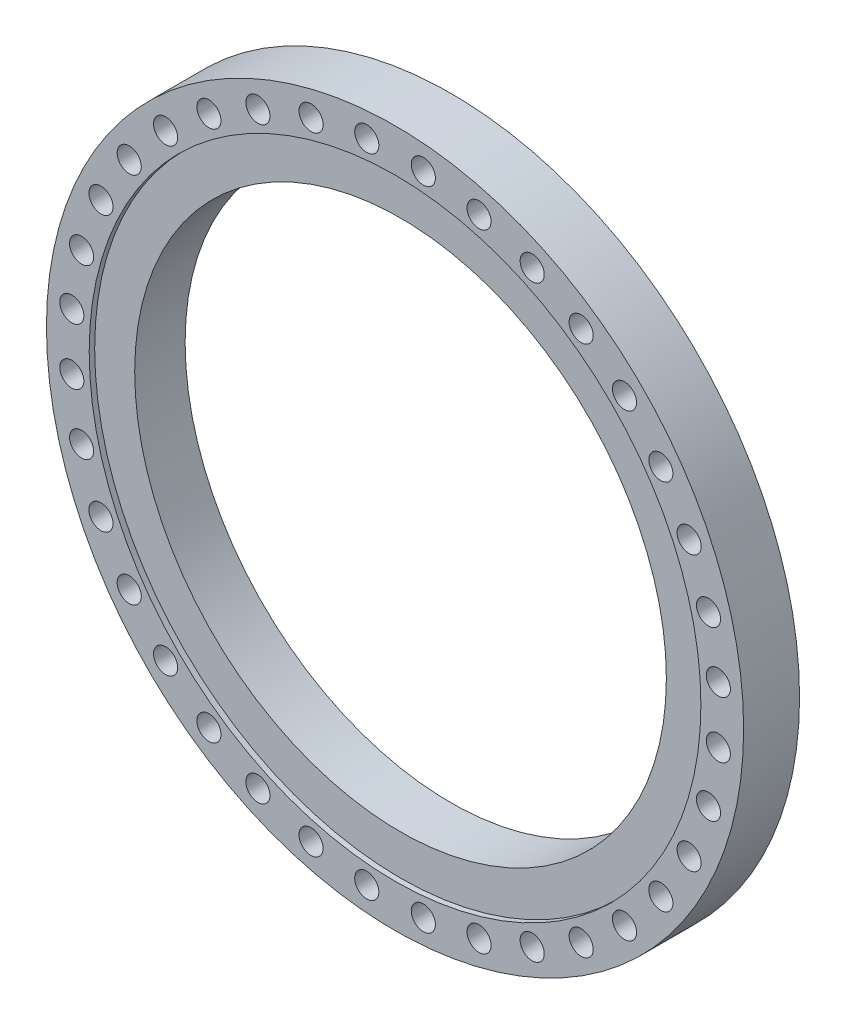
SolidWorks part; units mm, degrees
ref_plane "Front Plane" through (0, 0, 0) normal (0, 0, 1) x (1, 0, 0)
ref_plane "Top Plane" through (0, 0, 0) normal (0, 1, 0) x (1, 0, 0)
ref_plane "Right Plane" through (0, 0, 0) normal (1, 0, 0) x (0, 0, -1)
sketch "Sketch1" plane through (0, 0, 0) normal (1, 0, 0) x (0, 0, -1)
  line L0 (0, 0) -> (215.5415, 0) construction
  line L1 (0, 279) -> (0, 318)
  line L2 (0, 318) -> (51, 318)
  line L3 (51, 318) -> (51, 242.5)
  line L5 (2301, 254) -> (2301, 233.4)
  line L9 (0, 279) -> (5, 279)
  line L10 (5, 279) -> (5, 242.5)
  line L11 (5, 242.5) -> (51, 242.5)
  dimension "D1" = 485
  dimension "D2" = 636
  dimension "D3" = 558
  dimension "D6" = 51
  dimension "D7" = 5
  dimension "D8" = 2250
revolve "Revolve3" add sketch "Sketch1" angle 360 about L0
sketch "Sketch10" plane through (0, 0, 0) normal (0, 0, 1) x (1, 0, 0)
  line L0 (0, 0) -> (0, 534.1537) construction
  line L1 (0, 0) -> (-48.1006, 549.7918) construction
  line L2 (0, 0) -> (-125.8916, 469.8338) construction
  circle A0 centre (0, 0) radius 296 construction
  circle A1 centre (-25.7981, 294.8736) radius 11
  circle A2 centre (25.7981, 294.8736) radius 11
  circle A3 centre (76.6104, 285.914) radius 11
  circle A4 centre (125.095, 268.2671) radius 11
  circle A5 centre (169.7786, 242.469) radius 11
  circle A6 centre (209.3036, 209.3036) radius 11
  circle A7 centre (242.469, 169.7786) radius 11
  circle A8 centre (268.2671, 125.095) radius 11
  circle A9 centre (285.914, 76.6104) radius 11
  circle A10 centre (294.8736, 25.7981) radius 11
  circle A11 centre (294.8736, -25.7981) radius 11
  circle A12 centre (285.914, -76.6104) radius 11
  circle A13 centre (268.2671, -125.095) radius 11
  circle A14 centre (242.469, -169.7786) radius 11
  circle A15 centre (209.3036, -209.3036) radius 11
  circle A16 centre (169.7786, -242.469) radius 11
  circle A17 centre (125.095, -268.2671) radius 11
  circle A18 centre (76.6104, -285.914) radius 11
  circle A19 centre (25.7981, -294.8736) radius 11
  circle A20 centre (-25.7981, -294.8736) radius 11
  circle A21 centre (-76.6104, -285.914) radius 11
  circle A22 centre (-125.095, -268.2671) radius 11
  circle A23 centre (-169.7786, -242.469) radius 11
  circle A24 centre (-209.3036, -209.3036) radius 11
  circle A25 centre (-242.469, -169.7786) radius 11
  circle A26 centre (-268.2671, -125.095) radius 11
  circle A27 centre (-285.914, -76.6104) radius 11
  circle A28 centre (-294.8736, -25.7981) radius 11
  circle A29 centre (-294.8736, 25.7981) radius 11
  circle A30 centre (-285.914, 76.6104) radius 11
  circle A31 centre (-268.2671, 125.095) radius 11
  circle A32 centre (-242.469, 169.7786) radius 11
  circle A33 centre (-209.3036, 209.3036) radius 11
  circle A34 centre (-169.7786, 242.469) radius 11
  circle A35 centre (-125.095, 268.2671) radius 11
  circle A36 centre (-76.6104, 285.914) radius 11
  point P81 (0, 0)
  dimension "D1" = 592
  dimension "D2" = 22
  dimension "D3" = 5
  dimension "D4" = 10
  dimension "D5" = 36
extrude "Cut-Extrude5" cut sketch "Sketch10" against normal blind 463
